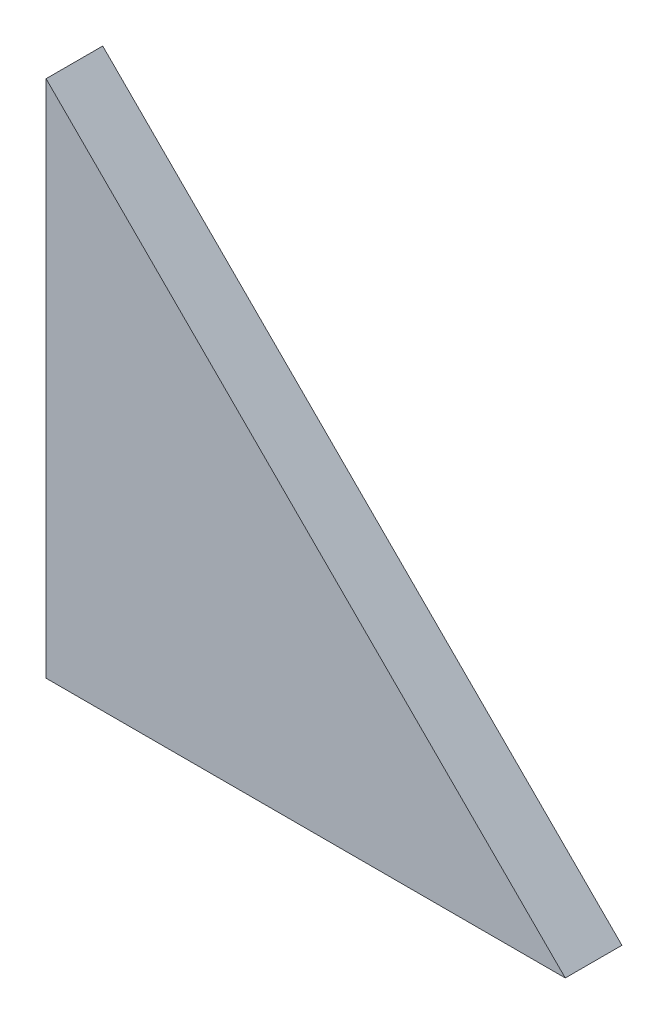
SolidWorks part; units mm, degrees
ref_plane "Front Plane" through (0, 0, 0) normal (0, 0, 1) x (1, 0, 0)
ref_plane "Top Plane" through (0, 0, 0) normal (0, 1, 0) x (1, 0, 0)
ref_plane "Right Plane" through (0, 0, 0) normal (1, 0, 0) x (0, 0, -1)
sketch "Sketch1" plane through (0, 0, 0) normal (0, 0, 1) x (1, 0, 0)
  line L0 (0, 110) -> (110, 0)
  line L1 (0, 0) -> (110, 0)
  line L2 (0, 0) -> (0, 110)
  dimension "Width" = 110
  dimension "Length" = 110
extrude "Extrude1" add sketch "Sketch1" along normal blind 12
